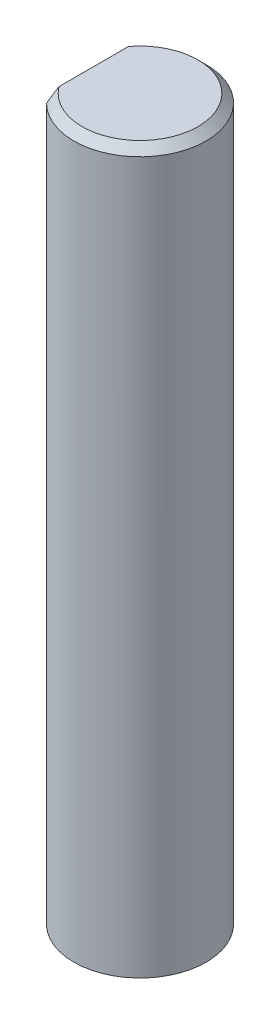
SolidWorks part; units mm, degrees
material "Plain Carbon Steel"
ref_plane "Front Plane" through (0, 0, 0) normal (0, 0, 1) x (1, 0, 0)
ref_plane "Top Plane" through (0, 0, 0) normal (0, 1, 0) x (1, 0, 0)
ref_plane "Right Plane" through (0, 0, 0) normal (1, 0, 0) x (0, 0, -1)
sketch "Sketch1" plane through (0, 0, 0) normal (0, 1, 0) x (1, 0, 0)
  circle A0 centre (0, 0) radius 2
  dimension "D1" = 4
extrude "Boss-Extrude1" add sketch "Sketch1" along normal blind 21.75
chamfer "Chamfer1" distance 0.25 angle 45 1 edges at (0, 21.75, 2)
sketch "Sketch2" plane through (0, 21.75, 0) normal (0, 1, 0) x (1, 0, 0)
  line L0 (-1.4, 1.4283) -> (-1.4, -1.4283)
  circle A0 centre (0, 0) radius 2 construction
  arc A2 (-1.4, 1.4283) -> (-1.4, -1.4283) centre (0, 0) cw
  circle A3 centre (0, 0) radius 2 construction
  point P5 (2, 0)
  dimension "D1" = 3.4
extrude "Cut-Extrude1" cut sketch "Sketch2" against normal blind 12 flip side to cut
